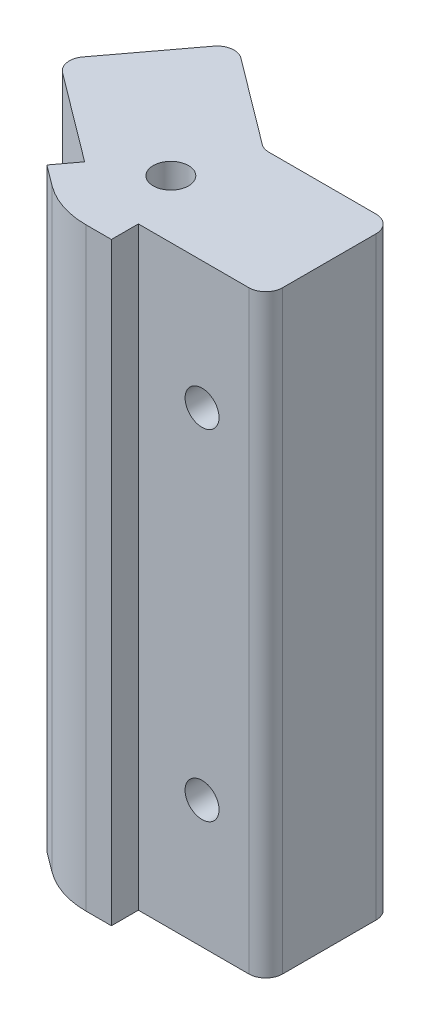
SolidWorks part; units mm, degrees
ref_plane "Front Plane" through (0, 0, 0) normal (0, 0, 1) x (1, 0, 0)
ref_plane "Top Plane" through (0, 0, 0) normal (0, 1, 0) x (1, 0, 0)
ref_plane "Right Plane" through (0, 0, 0) normal (1, 0, 0) x (0, 0, -1)
sketch "Sketch1" plane through (0, 0, 0) normal (0, 1, 0) x (1, 0, 0)
  line L0 (0, -10) -> (0, -6.825) construction
  line L2 (18, -6.825) -> (18, 54) construction
  line L3 (-6, -8) -> (-4.095, -5.46) construction
  line L5 (-18.495, 5.34) -> (18, 54) construction
  line L6 (-4.095, -5.46) -> (0, 0) construction
  line L8 (0, 0) -> (0, -6.825) construction
  line L9 (-3.1623, -9.4868) -> (0, 0) construction
  line L10 (0, 0) -> (18, 54) construction
  line L11 (-18.495, 5.34) -> (-9.495, 17.34)
  line L12 (-9.495, 17.34) -> (2.725, 8.175)
  line L13 (18, -6.825) -> (18, 8.175)
  line L14 (18, 8.175) -> (2.725, 8.175)
  line L15 (-6, -8) -> (-8.4, -6.2)
  line L16 (-8.4, -6.2) -> (-6.495, -3.66)
  line L17 (0, -10) -> (3, -10)
  line L18 (3, -10) -> (3, -6.825)
  line L19 (-18.495, 5.34) -> (-6.495, -3.66)
  line L20 (-6.495, -3.66) -> (-4.095, -5.46) construction
  line L21 (0, -6.825) -> (3, -6.825) construction
  line L22 (3, -6.825) -> (18, -6.825)
  line L23 (-6, -8) -> (-79.3333, 47) construction
  arc A0 (0, -10) -> (-6, -8) centre (0, 0) cw
  circle A1 centre (0, 0) radius 2.0788
  dimension "D1" = 10
  dimension "D3" = 4.1576
  dimension "D2" = 3.175
  dimension "D4" = 15
  dimension "D5" = 15
  dimension "D6" = 3
extrude "Boss-Extrude1" add sketch "Sketch1" along normal blind 70
sketch "Sketch2" plane through (0, 0, 6.825) normal (0, 0, 1) x (1, 0, 0)
  line L0 (10.5, 0) -> (10.5, 70) construction
  line L1 (3, 0) -> (18, 0) construction
  line L2 (3, 70) -> (18, 70) construction
  circle A0 centre (10.5, 15) radius 2
  circle A1 centre (10.5, 55) radius 2
  dimension "D1" = 4
  dimension "D2" = 15
  dimension "D3" = 15
extrude "Cut-Extrude1" cut sketch "Sketch2" against normal up to surface (15 mm away) up to face at (10.3625, 35, -8.175)
sketch "Sketch3" plane through (-4.095, 0, 5.46) normal (-0.6, 0, 0.8) x (0.8, 0, 0.6)
  line L0 (-10.5, 0) -> (-10.5, 70) construction
  line L1 (-18, 0) -> (-3, 0) construction
  line L2 (-18, 70) -> (-3, 70) construction
  circle A0 centre (-10.5, 15) radius 2
  circle A1 centre (-10.5, 55) radius 2
  dimension "D1" = 4
  dimension "D3" = 15
  dimension "D2" = 15
extrude "Cut-Extrude2" cut sketch "Sketch3" against normal up to surface (15 mm away) up to face at (-3.385, 35, -12.7575)
sketch "Sketch4" plane through (4.905, 0, -6.54) normal (0.6, 0, -0.8) x (-0.8, 0, -0.6)
  line L1 (10.5, 59.8714) -> (6.2812, 57.4357)
  line L2 (6.2812, 57.4357) -> (6.2813, 52.5643)
  line L3 (6.2813, 52.5643) -> (10.5, 50.1286)
  line L4 (10.5, 50.1286) -> (14.7188, 52.5643)
  line L5 (14.7188, 52.5643) -> (14.7187, 57.4357)
  line L6 (14.7187, 57.4357) -> (10.5, 59.8714)
  line L7 (10.5, 10.1286) -> (14.7188, 12.5643)
  line L8 (14.7188, 12.5643) -> (14.7188, 17.4357)
  line L9 (14.7188, 17.4357) -> (10.5, 19.8714)
  line L10 (10.5, 19.8714) -> (6.2813, 17.4357)
  line L11 (6.2813, 17.4357) -> (6.2813, 12.5643)
  line L12 (6.2813, 12.5643) -> (10.5, 10.1286)
  circle A0 centre (10.5, 55) radius 4.2188 construction
  circle A1 centre (10.5, 15) radius 4.2188 construction
  dimension "D1" = 8.4375
extrude "Cut-Extrude3" cut sketch "Sketch4" against normal blind 5
sketch "Sketch5" plane through (0, 0, -8.175) normal (0, 0, -1) x (-1, 0, 0)
  line L1 (-10.5, 50.1286) -> (-6.2813, 52.5643)
  line L2 (-6.2813, 52.5643) -> (-6.2813, 57.4357)
  line L3 (-6.2813, 57.4357) -> (-10.5, 59.8714)
  line L4 (-10.5, 59.8714) -> (-14.7188, 57.4357)
  line L5 (-14.7188, 57.4357) -> (-14.7188, 52.5643)
  line L6 (-14.7188, 52.5643) -> (-10.5, 50.1286)
  line L7 (-10.5, 10.1286) -> (-6.2813, 12.5643)
  line L8 (-6.2813, 12.5643) -> (-6.2813, 17.4357)
  line L9 (-6.2813, 17.4357) -> (-10.5, 19.8714)
  line L10 (-10.5, 19.8714) -> (-14.7188, 17.4357)
  line L11 (-14.7188, 17.4357) -> (-14.7188, 12.5643)
  line L12 (-14.7188, 12.5643) -> (-10.5, 10.1286)
  circle A0 centre (-10.5, 55) radius 4.2188 construction
  circle A1 centre (-10.5, 15) radius 4.2188 construction
  dimension "D1" = 8.4375
extrude "Cut-Extrude4" cut sketch "Sketch5" against normal blind 5
ref_plane "Plane1" through (4.2525, 0, -12.7575) normal (0.3162, 0, -0.9487) x (-0.9487, 0, -0.3162)
sketch "Sketch7" plane through (0, 70, 0) normal (0, 1, 0) x (1, 0, 0)
  line L0 (0, 0) -> (2.725, 8.175) construction
  line L1 (-1.5409, -4.6228) -> (3.233, -3.6459) construction
  line L2 (3.233, -3.6459) -> (4.7739, 0.9769) construction
  line L3 (4.7739, 0.9769) -> (1.5409, 4.6228) construction
  line L4 (1.5409, 4.6228) -> (-3.233, 3.6459) construction
  line L5 (-3.233, 3.6459) -> (-4.7739, -0.9769) construction
  line L6 (-4.7739, -0.9769) -> (-1.5409, -4.6228) construction
  line L7 (-4.7739, -0.9769) -> (-0.8336, 10.844)
  line L8 (2.725, 8.175) -> (-9.495, 17.34) construction
  line L9 (3.233, -3.6459) -> (7.1733, 8.175)
  line L10 (18, 8.175) -> (2.725, 8.175) construction
  line L11 (-4.7739, -0.9769) -> (-1.5409, -4.6228)
  line L12 (-1.5409, -4.6228) -> (3.233, -3.6459)
  line L13 (-0.8336, 10.844) -> (2.725, 8.175)
  line L14 (2.725, 8.175) -> (7.1733, 8.175)
  circle A0 centre (0, 0) radius 4.22 construction
  dimension "D1" = 8.44
extrude "Cut-Extrude5" cut sketch "Sketch7" along direction (0, -1, 0) on the side against the normal blind 5 from offset 5 offset against normal yes
fillet "Fillet1" radius 2 6 edges at (2.725, 67.5, -8.175) (18, 35, 6.825) (18, 35, -8.175) (2.725, 30, -8.175) (-9.495, 35, -17.34) (-18.495, 35, -5.34)
